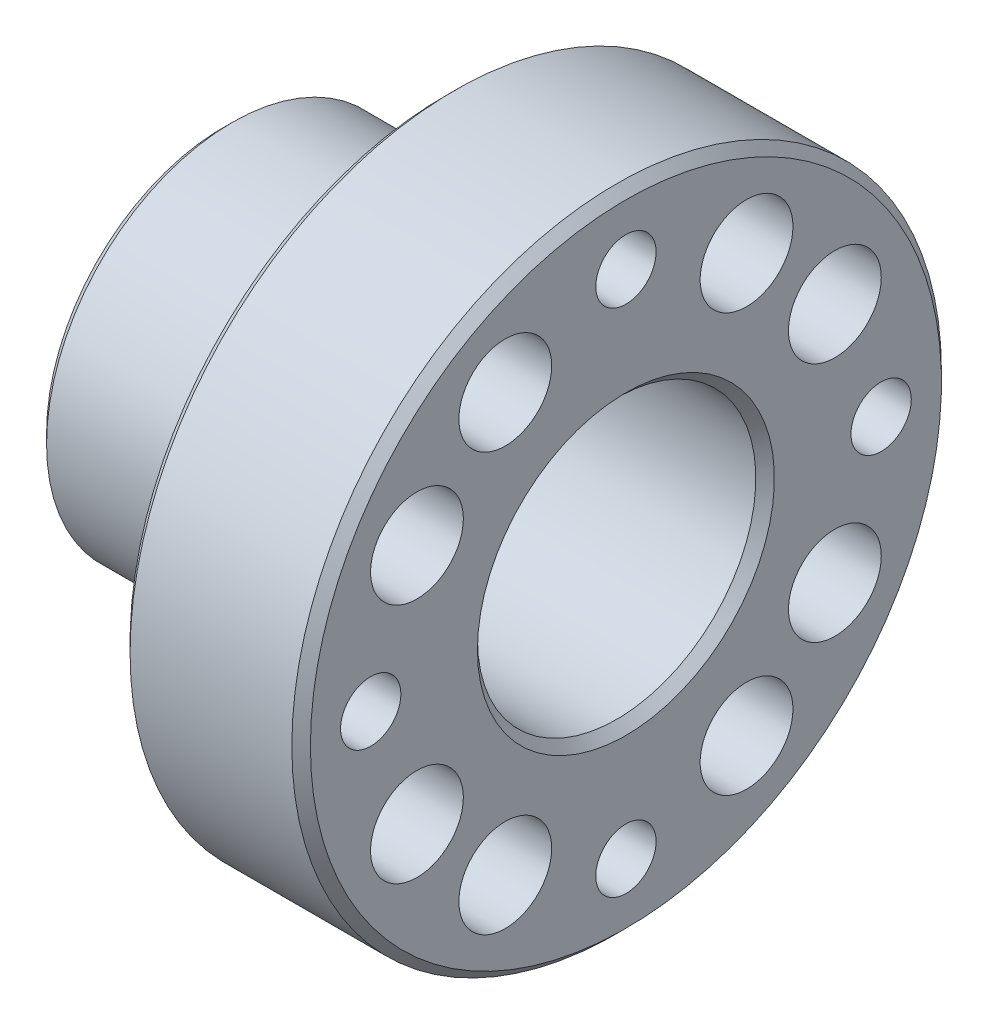
SolidWorks part; units mm, degrees
material "2014 Alloy"
ref_plane "Front Plane" through (0, 0, 0) normal (0, 0, 1) x (1, 0, 0)
ref_plane "Top Plane" through (0, 0, 0) normal (0, 1, 0) x (1, 0, 0)
ref_plane "Right Plane" through (0, 0, 0) normal (1, 0, 0) x (0, 0, -1)
sketch "Sketch1" plane through (0, 0, 0) normal (0, 1, 0) x (1, 0, 0)
  line L0 (0, 20) -> (24, 20)
  line L1 (24, 20) -> (24, 35)
  line L2 (24, 35) -> (43.43, 35)
  line L3 (43.43, 35) -> (43.43, 15)
  line L5 (0, 15) -> (0, 20)
  line L6 (0, 0) -> (28.2243, 0) construction
  line L7 (0, 15) -> (43.43, 15)
  dimension "D1" = 40
  dimension "D3" = 24
  dimension "D4" = 70
  dimension "D5" = 43.43
  dimension "D6" = 30
revolve "Revolve1" add sketch "Sketch1" angle 360 about L6
sketch "Sketch2" plane through (43.43, 0, 0) normal (1, 0, 0) x (0, 0, -1)
  circle A0 centre (0, 27.5) radius 3.25
  circle A1 centre (27.5, 0) radius 3.25
  circle A2 centre (-27.5, 0) radius 3.25
  circle A3 centre (0, -27.5) radius 3.25
  circle A4 centre (0, 0) radius 27.5 construction
  dimension "D1" = 6.5
  dimension "D2" = 55
extrude "Cut-Extrude1" cut sketch "Sketch2" against normal through all
chamfer "Chamfer1" distance 1 angle 45 6 edges at (43.43, 0, 35) (24, 0, 35) (24, 0, 20) (0, 0, 20) (0, 0, 15) (43.43, 0, 15)
sketch "Sketch3" plane through (43.43, 0, 0) normal (1, 0, 0) x (0, 0, -1)
  line L0 (17, 29.4449) -> (8, 13.8564) construction
  line L1 (13, 22.5167) -> (22.5167, 13) construction
  line L2 (17.7583, 17.7583) -> (0, 17.7583) construction
  line L3 (0, 17.7583) -> (0, 0) construction
  circle A0 centre (13, 22.5167) radius 5
  circle A1 centre (0, 0) radius 16 construction
  circle A2 centre (0, 0) radius 34 construction
  circle A3 centre (22.5167, 13) radius 5
  circle A4 centre (26, 0) radius 5 [skipped]
  circle A5 centre (22.5167, -13) radius 5
  circle A6 centre (13, -22.5167) radius 5
  circle A7 centre (0, -26) radius 5 [skipped]
  circle A8 centre (-13, -22.5167) radius 5
  circle A9 centre (-22.5167, -13) radius 5
  circle A10 centre (-26, 0) radius 5 [skipped]
  circle A11 centre (-22.5167, 13) radius 5
  circle A12 centre (-13, 22.5167) radius 5
  circle A13 centre (0, 26) radius 5 [skipped]
  point P33 (0, 0)
  dimension "D1" = 10
  dimension "D3" = 52
  dimension "D2" = 12
extrude "lightening holes" cut sketch "Sketch3" against normal through all
